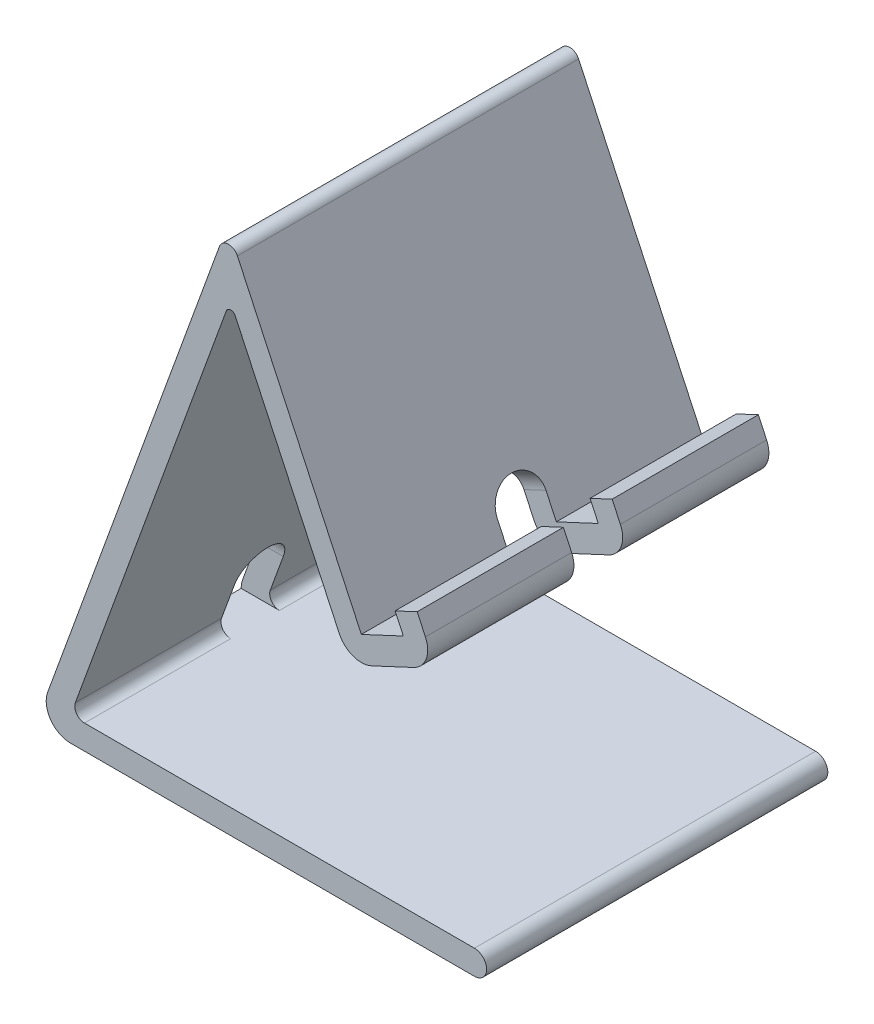
SolidWorks part; units mm, degrees
ref_plane "Płaszczyzna przednia" through (0, 0, 0) normal (0, 0, 1) x (1, 0, 0)
ref_plane "Płaszczyzna górna" through (0, 0, 0) normal (0, 1, 0) x (1, 0, 0)
ref_plane "Płaszczyzna prawa" through (0, 0, 0) normal (1, 0, 0) x (0, 0, -1)
sketch "Sketch1" plane through (0, 0, 0) normal (0, 0, 1) x (1, 0, 0)
  line L0 (90, 0) -> (7.1407, 0)
  line L1 (2.4423, 6.7101) -> (37.6809, 103.5274)
  line L2 (41.3729, 103.6886) -> (66.8025, 49.1546)
  line L3 (66.8025, 49.1546) -> (75.4124, 53.1695)
  line L4 (90, 5) -> (9.997, 5)
  line L5 (8.1177, 7.684) -> (39.0765, 92.7428)
  line L6 (40.9225, 92.8234) -> (62.271, 47.0416)
  line L7 (68.9156, 44.6231) -> (77.5255, 48.638)
  line L8 (75.4124, 53.1695) -> (73.722, 56.7947)
  line L9 (78.2535, 58.9078) -> (79.944, 55.2826)
  line L10 (73.722, 56.7947) -> (78.2535, 58.9078)
  line L11 (82.0571, 50.7511) -> (77.5255, 48.638)
  line L12 (39.3323, 108.0647) -> (66.8025, 49.1546) construction
  line L13 (0, 0) -> (39.3323, 108.0647) construction
  line L14 (7.1407, 5) -> (39.9022, 95.0115) construction
  line L15 (39.9022, 95.0115) -> (64.3841, 42.51) construction
  line L16 (90, 5) -> (7.1407, 5) construction
  line L17 (64.3841, 42.51) -> (77.5255, 48.638) construction
  line L18 (90, 0) -> (0, 0) construction
  arc A0 (90, 0) -> (90, 5) centre (90, 2.5) ccw
  arc A1 (41.3729, 103.6886) -> (37.6809, 103.5274) centre (39.5603, 102.8434) ccw
  arc A2 (39.0765, 92.7428) -> (40.9225, 92.8234) centre (40.0162, 92.4008) cw
  arc A3 (8.1177, 7.684) -> (9.997, 5) centre (9.997, 7) ccw
  arc A4 (77.5255, 48.638) -> (79.944, 55.2826) centre (75.4124, 53.1695) ccw
  arc A5 (68.9156, 44.6231) -> (62.271, 47.0416) centre (66.8025, 49.1546) cw
  arc A6 (7.1407, 0) -> (2.4423, 6.7101) centre (7.1407, 5) cw
  point P2 (-76.2806, 98.1212)
  point P18 (39.3323, 108.0647)
  dimension "D10" = 2
  dimension "D11" = 1
  dimension "D12" = 2
  dimension "D13" = 5
  dimension "D2" = 5
  dimension "D3" = 65
  dimension "D4" = 45
  dimension "D5" = 9.5
  dimension "D6" = 70
  dimension "D8" = 4
  dimension "D9" = 5
  dimension "D7" = 5
extrude "Boss-Extrude1" add sketch "Sketch1" against normal blind 70 contours A6 L0 A0 L4 A3 L5 A2 L6 A5 L7 A4 L9 L10 L8 L3 L2 A1 L1
sketch "Sketch2" plane through (73.6985, 34.3662, 0) normal (0.9063, 0.4226, 0) x (0, 0, -1)
  line L0 (40, 16.3173) -> (40, 21.3173)
  line L2 (70, 11.3173) -> (0, 11.3173) construction
  line L3 (70, 11.3173) -> (0, 11.3173)
  line L4 (30, 16.3173) -> (30, 11.3173)
  line L5 (35, 76.4889) -> (35, 16.3173) construction
  line L8 (0, 76.4889) -> (0, 16.3173)
  line L9 (0, 16.3173) -> (70, 16.3173)
  line L10 (70, 16.3173) -> (70, 76.4889)
  line L11 (70, 76.4889) -> (0, 76.4889)
  line L12 (0, 76.4889) -> (0, 16.3173)
  line L13 (0, 16.3173) -> (70, 16.3173)
  line L14 (70, 16.3173) -> (70, 76.4889)
  line L15 (70, 76.4889) -> (0, 76.4889)
  line L16 (40, 16.3173) -> (40, 11.3173)
  line L17 (30, 16.3173) -> (30, 21.3173)
  line L18 (40, 11.3173) -> (30, 11.3173)
  arc A0 (40, 21.3173) -> (30, 21.3173) centre (35, 21.3173) ccw
  dimension "D4" = 5
  dimension "D2" = 10
  dimension "D1" = 0
extrude "Cut-Extrude2" cut sketch "Sketch2" against normal blind 40 and the other way blind 40 contours A0 L17 L4 L18 L16 L0
sketch "Sketch5" plane through (0, 0, 0) normal (1, 0, 0) x (0, 0, -1)
  line L0 (40, 10) -> (40, 15)
  line L1 (40, 5) -> (30, 5)
  line L2 (30, 10) -> (30, 5)
  line L3 (35, 72.8556) -> (35, 5) construction
  line L8 (40, 10) -> (40, 5)
  line L9 (30, 10) -> (30, 15)
  line L10 (70, 5) -> (0, 5) construction
  line L11 (70, 5) -> (0, 5)
  arc A0 (40, 15) -> (30, 15) centre (35, 15) ccw
  dimension "D1" = 10
  dimension "D2" = 10
extrude "Cut-Extrude4" cut sketch "Sketch5" along normal blind 20 contours A0 L9 L2 L1 L8 L0
